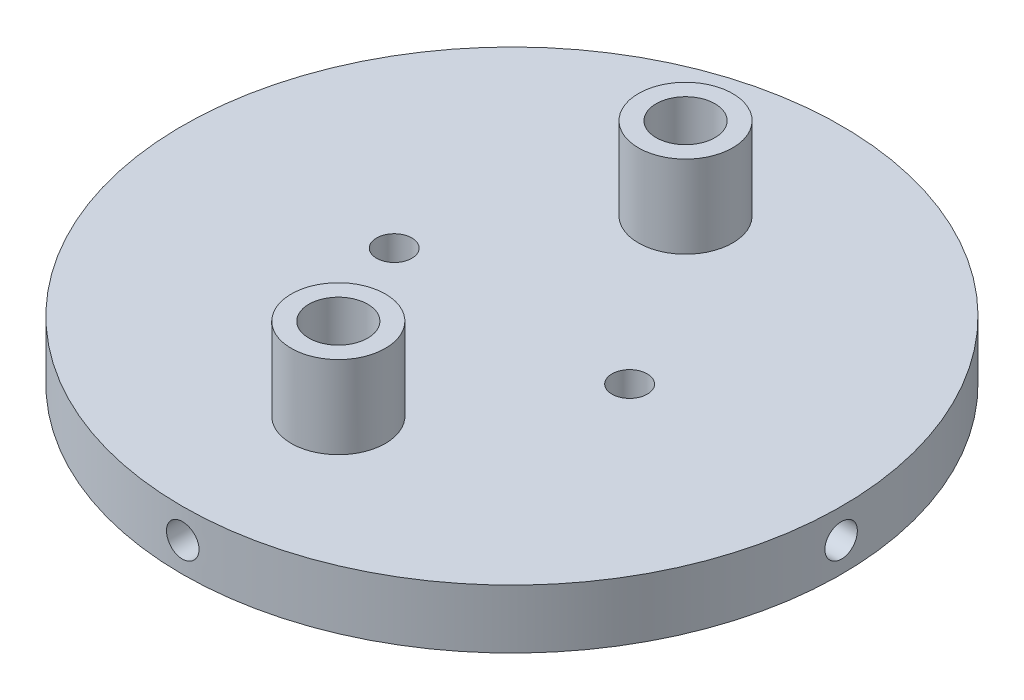
SolidWorks part; units mm, degrees
ref_plane "Front Plane" through (0, 0, 0) normal (0, 0, 1) x (1, 0, 0)
ref_plane "Top Plane" through (0, 0, 0) normal (0, 1, 0) x (1, 0, 0)
ref_plane "Right Plane" through (0, 0, 0) normal (1, 0, 0) x (0, 0, -1)
other "Center of Mass"
sketch "Sketch1" plane through (0, 0, 0) normal (0, 1, 0) x (1, 0, 0)
  circle A2 centre (0, 0) radius 35.56
extrude "Boss-Extrude1" add sketch "Sketch1" along normal blind 6.35
sketch "Sketch2" plane through (0, 6.35, 0) normal (0, 1, 0) x (1, 0, 0)
  line L0 (0, 0) -> (-37.465, 0)
  circle A0 centre (0, 0) radius 37.465 construction
sketch "Sketch3" plane through (0, 6.35, 0) normal (0, 1, 0) x (1, 0, 0)
  line L1 (0, 0) -> (-37.465, 0) construction
  circle A2 centre (-12.7, 0) radius 1.905
  circle A3 centre (12.7, 0) radius 1.905
extrude "Cut-Extrude1" cut sketch "Sketch3" against normal blind 6.35
sketch "Sketch4" plane through (0, 6.35, 0) normal (0, 1, 0) x (1, 0, 0)
  circle A6 centre (0, 18.7325) radius 2.54
  circle A7 centre (0, 18.7325) radius 5.08
extrude "Boss-Extrude2" add sketch "Sketch4" along normal blind 8.89
mirror "Mirror1" about plane through (0, 0, 0) normal (0, 0, 1) of "Boss-Extrude2"
sketch "Sketch5" plane through (0, 6.35, 0) normal (0, 1, 0) x (1, 0, 0)
  circle A0 centre (0, 18.7325) radius 1.5
  circle A1 centre (0, -18.7325) radius 1.5
extrude "Cut-Extrude2" cut sketch "Sketch5" against normal blind 10
sketch "Sketch6" plane through (0, 15.24, 0) normal (0, 1, 0) x (1, 0, 0)
  circle A0 centre (0, 18.7325) radius 3.175
  circle A1 centre (0, -18.7325) radius 3.175
extrude "Cut-Extrude3" cut sketch "Sketch6" against normal up to surface (8.89 mm away) up to face at (0, 6.35, 23.8125)
sketch "Sketch7" plane through (0, 6.35, 0) normal (0, 1, 0) x (1, 0, 0)
  line L0 (-37.465, 0) -> (-34.29, 0)
  line L1 (0, 0) -> (-37.465, 0) construction
  line L2 (-12.7, 3.81) -> (-12.7, 6.35)
  line L3 (-12.7, -3.81) -> (-12.7, -6.35)
  line L4 (-33.6969, 6.35) -> (33.6969, 6.35)
  line L5 (-33.6969, -6.35) -> (33.6969, -6.35)
  line L6 (-5.08, 18.7325) -> (-5.08, 33.9116)
  line L7 (5.08, 18.7325) -> (5.08, 33.9116)
  line L8 (5.08, 18.7325) -> (5.08, -33.9116)
  line L9 (-5.08, 18.7325) -> (-5.08, -33.9116)
  circle A0 centre (0, 0) radius 34.29
  circle A1 centre (-12.7, 0) radius 3.81 construction
  circle A2 centre (0, 18.7325) radius 5.08 construction
  circle A3 centre (0, 18.7325) radius 5.08 construction
sketch "Sketch8" plane through (0, 0, 0) normal (1, 0, 0) x (0, 0, -1)
  circle A0 centre (0, 3.175) radius 1.7526
extrude "Cut-Extrude4" cut sketch "Sketch8" against normal blind 17.78 from offset 40.64
pattern_circular "CirPattern1" count 4 over 360 about axis through (0, 0, 0) along (0, 1, 0) of "Cut-Extrude4"
